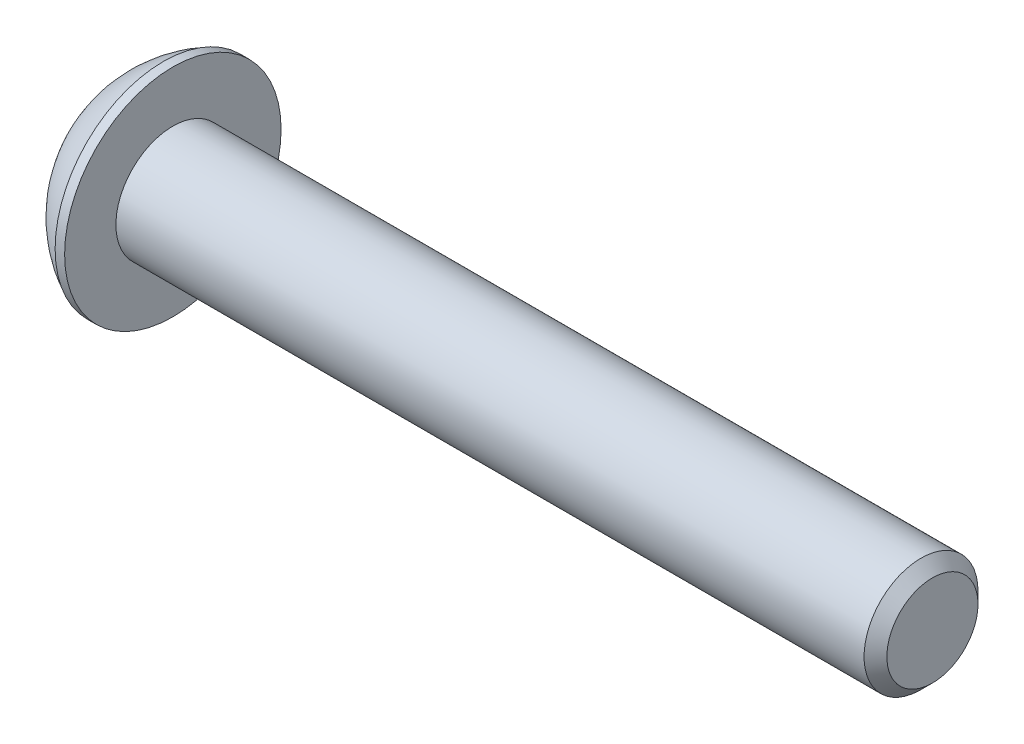
SolidWorks part; units mm, degrees
material "純碳鋼"
ref_plane "Front Plane" through (0, 0, 0) normal (0, 0, 1) x (1, 0, 0)
ref_plane "Top Plane" through (0, 0, 0) normal (0, 1, 0) x (1, 0, 0)
ref_plane "Right Plane" through (0, 0, 0) normal (1, 0, 0) x (0, 0, -1)
sketch "Sketch2" plane through (0, 0, 0) normal (1, 0, 0) x (0, 0, -1)
  circle A0 centre (0, 0) radius 1.5
  dimension "D1" = 3
extrude "Boss-Extrude1" add sketch "Sketch2" against normal blind 20
chamfer "Chamfer1" distance 0.3 angle 45 1 edges at (0, 0, -1.5)
sketch "Sketch6" plane through (0, 0, 0) normal (0, 0, 1) x (1, 0, 0)
  line L0 (-21.65, 0) -> (-21.65, 1.5)
  line L1 (-21.65, 0) -> (-20, 0)
  line L2 (-20.25, 2.85) -> (-20, 2.85)
  line L6 (-20, 2.85) -> (-20, 0)
  line L8 (-20, 0) -> (-14.6471, 0) construction
  line L10 (-20, 1.5) -> (-20, -1.5) construction
  arc A0 (-21.65, 1.5) -> (-20.25, 2.85) centre (-18.8527, 0) cw
  dimension "D3" = 0.25
  dimension "D1" = 5.7
  dimension "D2" = 1.65
  dimension "D4" = 3
revolve "Revolve1" add sketch "Sketch6" angle 360 about L8
sketch "Sketch7" plane through (-21.65, 0, 0) normal (-1, 0, 0) x (0, 0, 1)
  line L1 (0, 1.1547) -> (-1, 0.5774)
  line L2 (-1, 0.5774) -> (-1, -0.5774)
  line L3 (-1, -0.5774) -> (0, -1.1547)
  line L4 (0, -1.1547) -> (1, -0.5774)
  line L5 (1, -0.5774) -> (1, 0.5774)
  line L6 (1, 0.5774) -> (0, 1.1547)
  circle A0 centre (0, 0) radius 1 construction
  dimension "D1" = 2
extrude "Cut-Extrude1" cut sketch "Sketch7" against normal blind 1.2
sketch "Sketch8" plane through (-21.65, 0, 0) normal (-1, 0, 0) x (0, 0, 1)
  circle A0 centre (0, 0) radius 1.2047
  dimension "D1" = 0.05
extrude "Cut-Extrude2" cut sketch "Sketch8" against normal blind 1 draft 45
